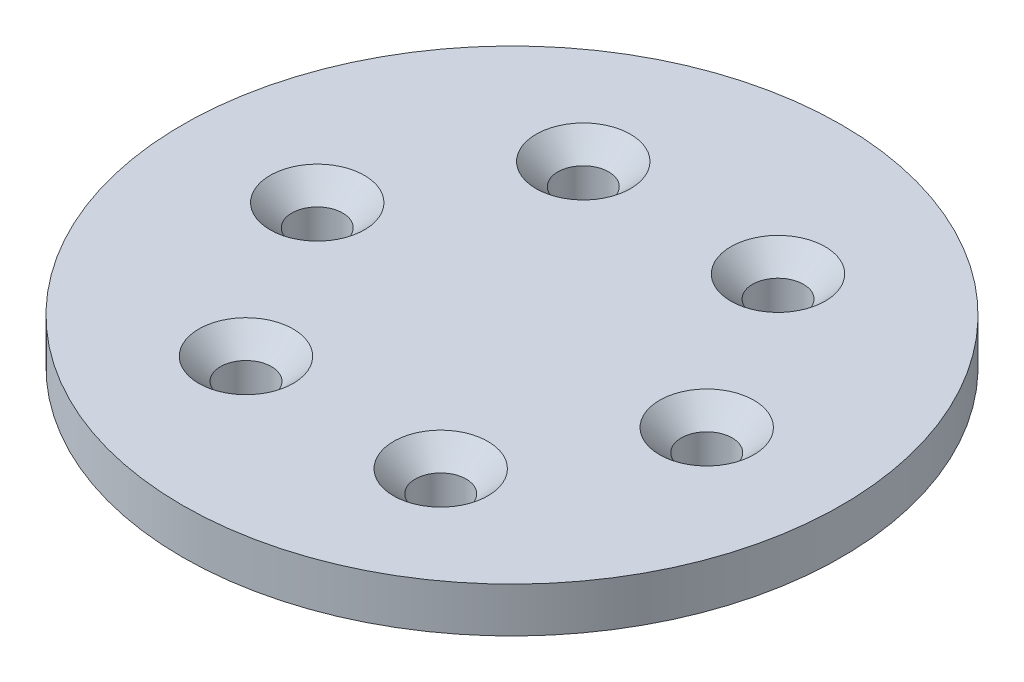
SolidWorks part; units mm, degrees
ref_plane "Спереди" through (0, 0, 0) normal (0, 0, 1) x (1, 0, 0)
ref_plane "Сверху" through (0, 0, 0) normal (0, 1, 0) x (1, 0, 0)
ref_plane "Справа" through (0, 0, 0) normal (1, 0, 0) x (0, 0, -1)
sketch "Эскиз1" plane through (0, 0, 0) normal (1, 0, 0) x (0, 0, -1)
  line L1 (22, 1) -> (-22, 1) construction
  line L2 (22, 1) -> (-22, 1) construction
  line L5 (22, 1) -> (22, 4)
  line L14 (19.5, 0) -> (-19.5, 0) construction
  line L15 (19.5, 0) -> (-19.5, 0) construction
  line L16 (0, 0) -> (19.5, 0)
  line L17 (22, 1) -> (19.5, 0)
  line L18 (0, 0) -> (0, 4)
  line L19 (0, 4) -> (22, 4)
  dimension "D2" = 3
revolve "Повернуть1" add sketch "Эскиз1" angle 360 about L18
hole_wizard "Зенковка для винта с полупотайной головкой M31" positions "Эскиз5" profile "Эскиз7" countersink size "M3" standard "DIN" end condition through all
sketch "Эскиз5" plane through (0, 4, 0) normal (0, 1, 0) x (1, 0, 0)
  line L1 (0, 0) -> (22, 0) construction
  circle A2 centre (0, 0) radius 22 construction
  point P17 (13, 0)
  point P24 (6.5, -11.2583)
  point P25 (-6.5, -11.2583)
  point P26 (-13, 0)
  point P27 (-6.5, 11.2583)
  point P28 (6.5, 11.2583)
  dimension "D1" = 13
  dimension "D2" = 6
sketch "Эскиз7" plane through (6.5, 4, -11.2583) normal (1, 0, 0) x (0, 0, 1)
  line L0 (0, 0) -> (0, 4)
  line L1 (0, 4) -> (1.7, 4)
  line L2 (1.7, 4) -> (1.7, 1.45)
  line L3 (1.7, 1.45) -> (3.15, 0)
  line L5 (3.15, 0) -> (0, 0)
  line L6 (-1.7, 1.45) -> (-3.15, 0) construction
  line L11 (0, -6.35) -> (0, 107.95) construction
  dimension "Диаметр сквозного отверстия" = 3.4
  dimension "Глубина сквозного отверстия" = 4
  dimension "Диаметр передней зенковки" = 6.3
  dimension "Угол передней зенковки" = 90
